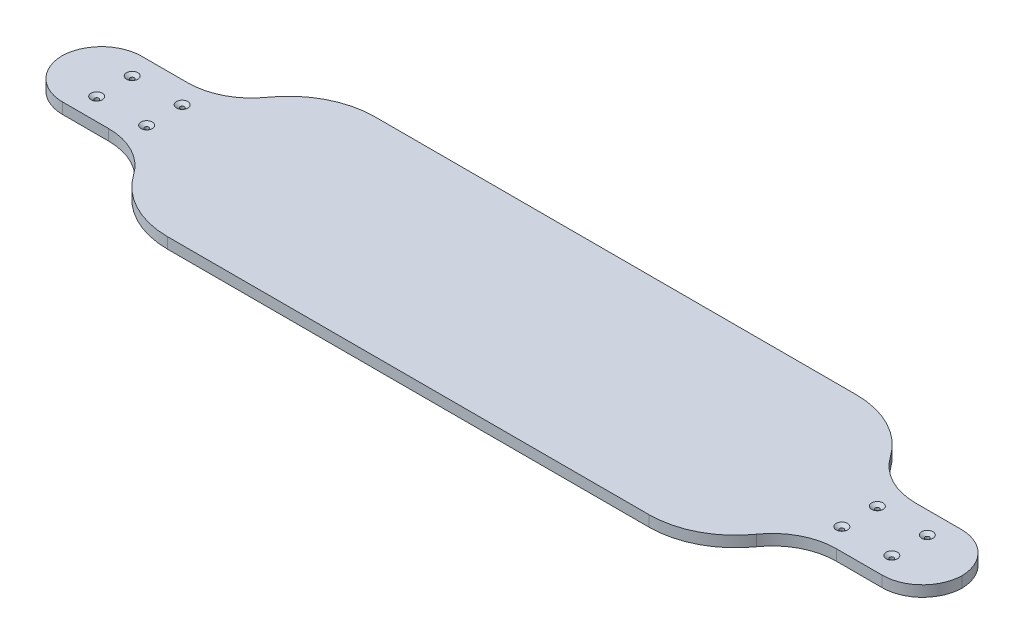
SolidWorks part; units mm, degrees
ref_plane "Front Plane" through (0, 0, 0) normal (0, 0, 1) x (1, 0, 0)
ref_plane "Top Plane" through (0, 0, 0) normal (0, 1, 0) x (1, 0, 0)
ref_plane "Right Plane" through (0, 0, 0) normal (1, 0, 0) x (0, 0, -1)
sketch "Sketch1" plane through (0, 0, 0) normal (0, 1, 0) x (1, 0, 0)
  line L0 (223.7042, -64.1317) -> (641.7042, -64.1317) construction
  line L1 (279.8476, -120.65) -> (-279.8476, -120.65)
  line L3 (279.8476, 120.65) -> (-279.8476, 120.65)
  line L5 (362.1995, -77.7811) -> (-362.1995, 77.7811) construction
  line L6 (362.1995, 77.7811) -> (-362.1995, -77.7811) construction
  line L7 (-482.6928, 14.853) -> (-64.6928, 14.853) construction
  line L8 (-476.4693, 46.0246) -> (-423.2042, 46.0246)
  line L9 (-523.4247, 0) -> (523.4247, 0) construction
  line L10 (0, 120.65) -> (0, -120.65) construction
  line L11 (-476.4693, -46.0246) -> (-423.2042, -46.0246)
  line L12 (476.4693, -46.0246) -> (423.2042, -46.0246)
  line L13 (476.4693, 46.0246) -> (423.2042, 46.0246)
  arc A0 (-523.4247, 0) -> (-476.4693, 46.0246) centre (-476.4693, -0.9403) cw
  arc A1 (-423.2042, 46.0246) -> (-362.1995, 77.7811) centre (-423.2042, 120.4982) ccw
  arc A2 (-362.1995, 77.7811) -> (-279.8476, 120.65) centre (-279.8476, 20.1159) cw
  arc A3 (-523.4247, 0) -> (-476.4693, -46.0246) centre (-476.4693, 0.9403) ccw
  arc A4 (-423.2042, -46.0246) -> (-362.1995, -77.7811) centre (-423.2042, -120.4982) cw
  arc A5 (-362.1995, -77.7811) -> (-279.8476, -120.65) centre (-279.8476, -20.1159) ccw
  arc A6 (362.1995, -77.7811) -> (279.8476, -120.65) centre (279.8476, -20.1159) cw
  arc A7 (423.2042, -46.0246) -> (362.1995, -77.7811) centre (423.2042, -120.4982) ccw
  arc A8 (523.4247, 0) -> (476.4693, -46.0246) centre (476.4693, 0.9403) cw
  arc A9 (523.4247, 0) -> (476.4693, 46.0246) centre (476.4693, -0.9403) ccw
  arc A10 (423.2042, 46.0246) -> (362.1995, 77.7811) centre (423.2042, 120.4982) cw
  arc A11 (362.1995, 77.7811) -> (279.8476, 120.65) centre (279.8476, 20.1159) ccw
  circle A12 centre (-404.1647, 20.6375) radius 2.38
  circle A13 centre (-462.2663, 20.6375) radius 2.38
  circle A14 centre (-404.1647, -20.6375) radius 2.38
  circle A15 centre (-462.2663, -20.6375) radius 2.38
  circle A16 centre (462.2663, -20.6375) radius 2.38
  circle A17 centre (404.1647, -20.6375) radius 2.38
  circle A18 centre (462.2663, 20.6375) radius 2.38
  circle A19 centre (404.1647, 20.6375) radius 2.38
  point P0 (0, 0)
  point P28 (-326.2685, -109.2911)
  point P29 (326.2685, -109.2911)
  dimension "D3" = 46.9649
  dimension "D4" = 476.4693
  dimension "D1" = 100.5341
  dimension "D7" = 74.4736
  dimension "D8" = 4.76
  dimension "D2" = 241.3
  dimension "D5" = 279.8476
  dimension "D6" = 92.0492
  dimension "D9" = 61.1584
  dimension "D10" = 58.1016
  dimension "D11" = 41.275
extrude "Boss-Extrude1" add sketch "Sketch1" along normal blind 12.64
chamfer "Chamfer1" distance 4.2291 distance2 2.94 8 edges at (404.1647, 12.64, -23.0175) (404.1647, 12.64, 23.0175) (-404.1647, 12.64, -18.2575) (-404.1647, 12.64, 18.2575) (-462.2663, 12.64, 18.2575) (462.2663, 12.64, 23.0175) (462.2663, 12.64, -23.0175) (-462.2663, 12.64, -18.2575)
